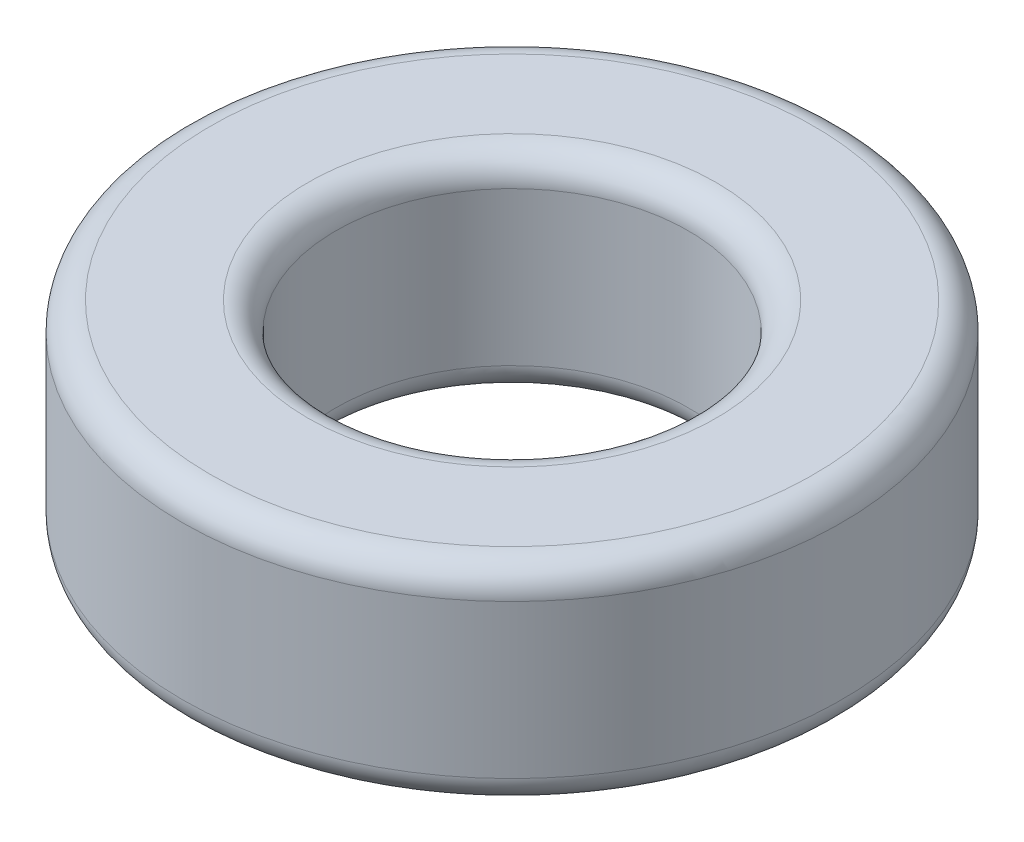
SolidWorks part; units mm, degrees
ref_plane "Front Plane" through (0, 0, 0) normal (0, 0, 1) x (1, 0, 0)
ref_plane "Top Plane" through (0, 0, 0) normal (0, 1, 0) x (1, 0, 0)
ref_plane "Right Plane" through (0, 0, 0) normal (1, 0, 0) x (0, 0, -1)
sketch "Sketch1" plane through (0, 0, 0) normal (0, 1, 0) x (1, 0, 0)
  circle A0 centre (0, 0) radius 12.65
  circle A1 centre (0, 0) radius 23.65
  dimension "D2" = 47.3
  dimension "D1" = 11
extrude "Boss-Extrude1" add sketch "Sketch1" along normal blind 15
fillet "Fillet1" radius 2 4 edges at (0, 0, 23.65) (0, 15, 23.65) (0, 0, 12.65) (0, 15, 12.65)
